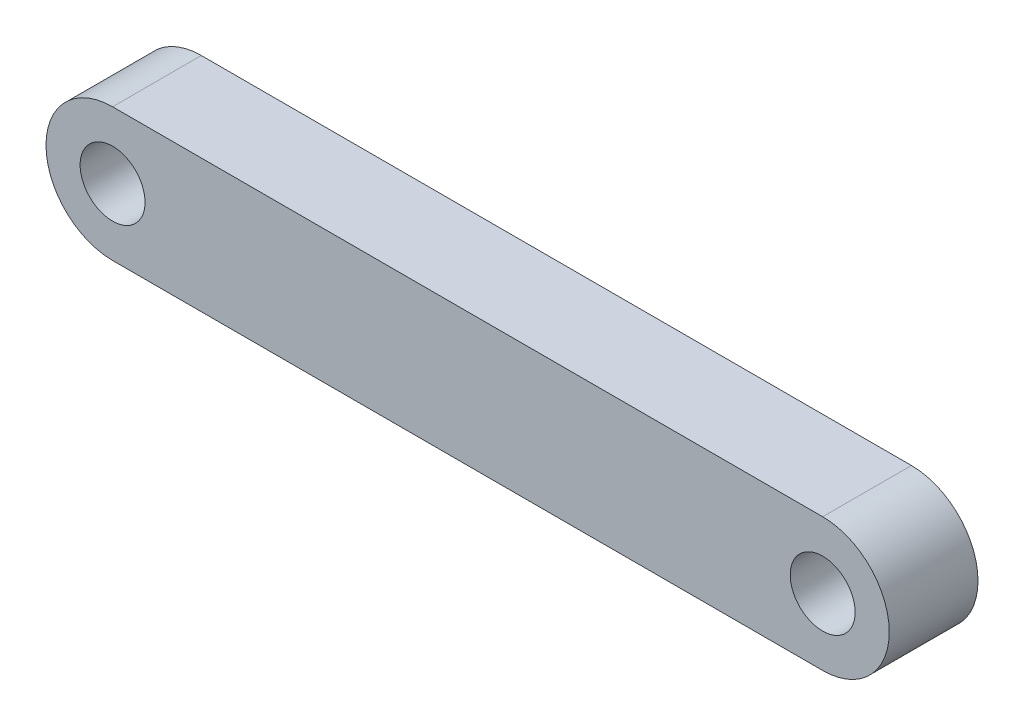
SolidWorks part; units mm, degrees
ref_plane "Front Plane" through (0, 0, 0) normal (0, 0, 1) x (1, 0, 0)
ref_plane "Top Plane" through (0, 0, 0) normal (0, 1, 0) x (1, 0, 0)
ref_plane "Right Plane" through (0, 0, 0) normal (1, 0, 0) x (0, 0, -1)
sketch "Sketch1" plane through (0, 0, 0) normal (0, 0, 1) x (1, 0, 0)
  line L0 (0, 0) -> (80, 0) construction
  line L1 (0, 7.5) -> (80, 7.5)
  line L2 (0, -7.5) -> (80, -7.5)
  arc A0 (0, 7.5) -> (0, -7.5) centre (0, 0) ccw
  arc A1 (80, -7.5) -> (80, 7.5) centre (80, 0) ccw
  circle A2 centre (0, 0) radius 3.6576
  circle A3 centre (80, 0) radius 3.6576
  point P3 (40, 0)
  dimension "D3" = 7.3152
  dimension "D1" = 80
  dimension "D2" = 15
extrude "Boss-Extrude1" add sketch "Sketch1" along normal blind 10
